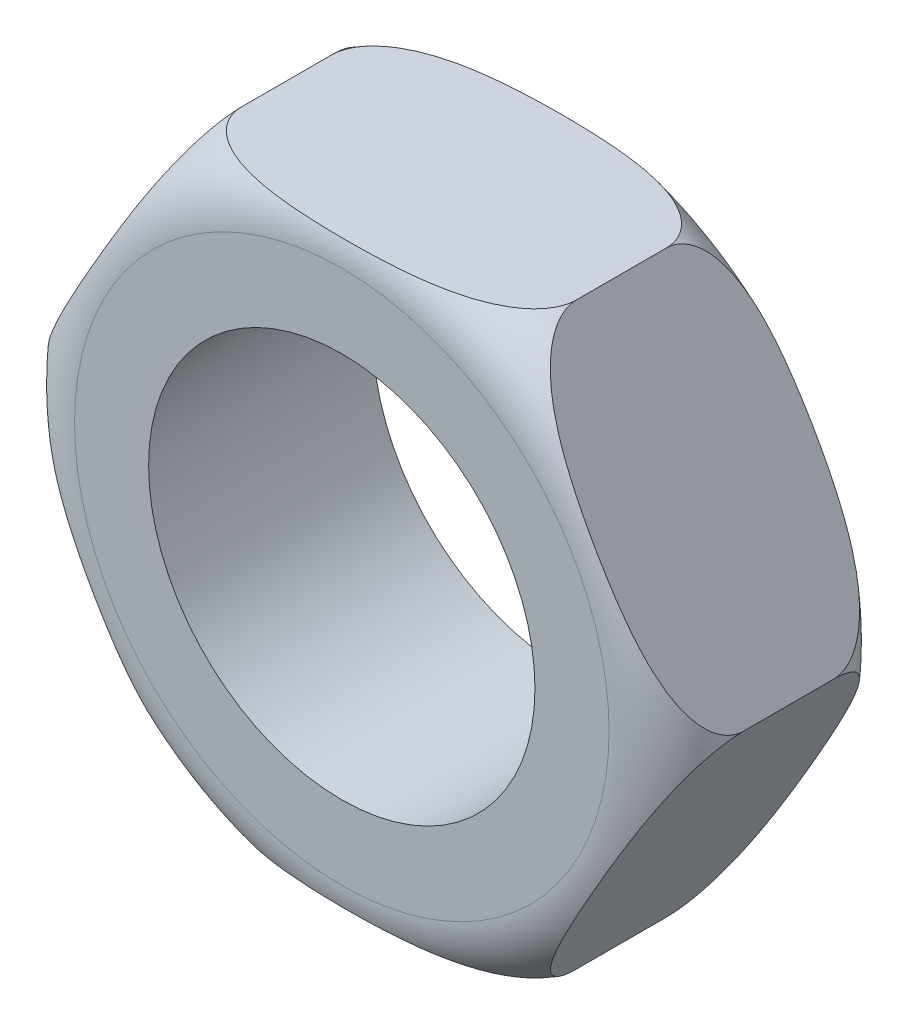
SolidWorks part; units mm, degrees
ref_plane "Front" through (0, 0, 0) normal (0, 0, 1) x (1, 0, 0)
ref_plane "Top" through (0, 0, 0) normal (0, 1, 0) x (1, 0, 0)
ref_plane "Right" through (0, 0, 0) normal (1, 0, 0) x (0, 0, -1)
sketch "Sketch1" plane through (0, 0, 0) normal (0, 0, 1) x (1, 0, 0)
  line L1 (13.7482, 0) -> (6.8741, 11.9063)
  line L2 (6.8741, 11.9063) -> (-6.8741, 11.9063)
  line L3 (-6.8741, 11.9063) -> (-13.7482, 0)
  line L4 (-13.7482, 0) -> (-6.8741, -11.9062)
  line L5 (-6.8741, -11.9062) -> (6.8741, -11.9062)
  line L6 (6.8741, -11.9062) -> (13.7482, 0)
  circle A0 centre (0, 0) radius 11.9062 construction
  circle A1 centre (0, 0) radius 7.9375
  dimension "NN" = 15.875
  dimension "D1" = 23.8125
extrude "Base-Extrude" add sketch "Sketch1" along normal mid plane 9.2202
sketch "Sketch2" plane through (0, 0, 0) normal (0, 1, 0) x (1, 0, 0)
  line L0 (0, 0) -> (0, 26.9043) construction
  line L1 (0, -4.6101) -> (0, 4.6101) construction
  line L2 (0, 0) -> (39.4148, 0) construction
  line L3 (13.7482, 4.6101) -> (13.7482, 1.844)
  line L4 (13.7482, -4.6101) -> (13.7482, 4.6101) construction
  line L5 (13.7482, 4.6101) -> (10.9821, 4.6101)
  line L6 (13.7482, 4.6101) -> (6.8741, 4.6101) construction
  line L7 (13.7482, -4.6101) -> (10.9821, -4.6101)
  line L8 (13.7482, -4.6101) -> (13.7482, -1.844)
  arc A0 (13.7482, 1.844) -> (10.9821, 4.6101) centre (10.9821, 1.844) ccw
  arc A1 (13.7482, -1.844) -> (10.9821, -4.6101) centre (10.9821, -1.844) cw
  dimension "D1" = 2.7661
revolve "Cut-Revolve1" cut sketch "Sketch2" angle 360 about L0
